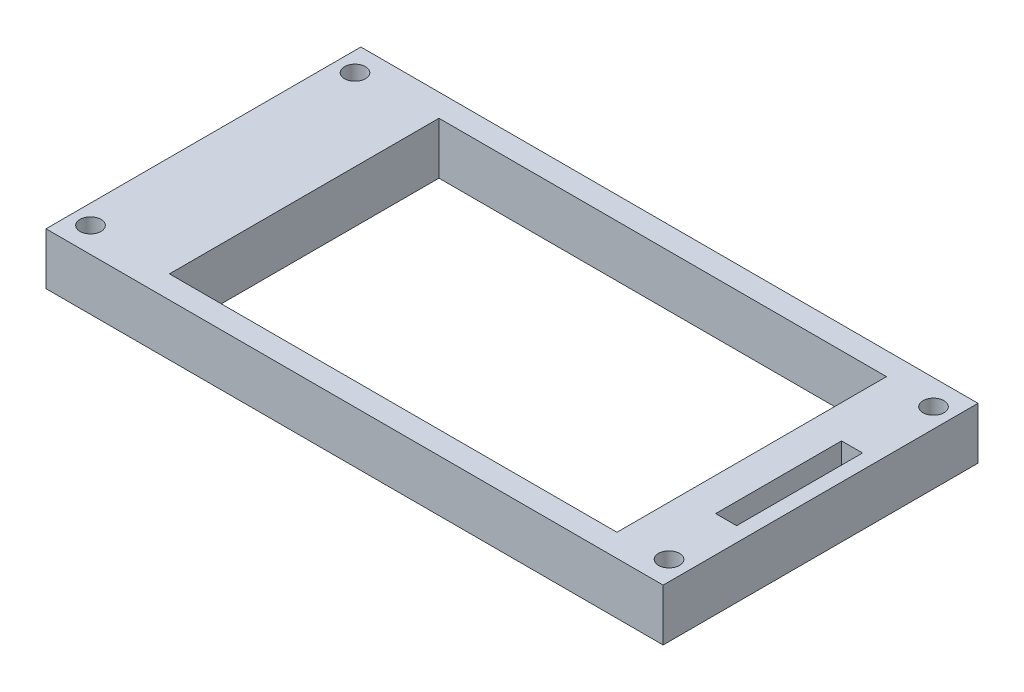
SolidWorks part; units mm, degrees
ref_plane "Front" through (0, 0, 0) normal (0, 0, 1) x (1, 0, 0)
ref_plane "Top" through (0, 0, 0) normal (0, 1, 0) x (1, 0, 0)
ref_plane "Right" through (0, 0, 0) normal (1, 0, 0) x (0, 0, -1)
sketch "Sketch1" plane through (0, 0, 0) normal (0, 1, 0) x (1, 0, 0)
  line L0 (12, -2.7) -> (65.3, -2.7)
  line L1 (0, 0) -> (73.5, 0)
  line L2 (0, 0) -> (0, -37.5)
  line L3 (0, -37.5) -> (73.5, -37.5)
  line L4 (73.5, 0) -> (73.5, -37.5)
  line L5 (69.25, -12) -> (71.75, -12)
  line L6 (69.25, -12) -> (69.25, -27)
  line L7 (69.25, -27) -> (71.75, -27)
  line L8 (71.75, -12) -> (71.75, -27)
  line L9 (4, 0) -> (68.1, 0)
  line L10 (4, 0) -> (4, -37.5)
  line L11 (4, -37.5) -> (68.1, -37.5)
  line L12 (68.1, 0) -> (68.1, -37.5)
  line L13 (12, -2.7) -> (12, -34.8)
  line L14 (12, -34.8) -> (65.3, -34.8)
  line L15 (65.3, -2.7) -> (65.3, -34.8)
  circle A0 centre (2.3, -3) radius 1.25
  circle A1 centre (71.2, -3) radius 1.25
  circle A2 centre (71.2, -34.5) radius 1.25
  circle A3 centre (2.3, -34.5) radius 1.25
  point P17 (70.5, -12)
  point P18 (70.5, -27)
  point P23 (68.1, -18.75)
  dimension "D3" = 2.5
  dimension "D4" = 3
  dimension "D5" = 2.3
  dimension "D6" = 2.5
  dimension "D7" = 3
  dimension "D8" = 2.3
  dimension "D9" = 2.5
  dimension "D10" = 3
  dimension "D11" = 2.3
  dimension "D12" = 2.5
  dimension "D13" = 3
  dimension "D14" = 2.3
  dimension "D1" = 37.5
  dimension "D2" = 73.5
  dimension "D15" = 2.5
  dimension "D16" = 15
  dimension "D17" = 12
  dimension "D18" = 3
  dimension "D19" = 37.5
  dimension "D20" = 64.1
  dimension "D21" = 5.4
  dimension "D22" = 53.3
  dimension "D23" = 2.7
  dimension "D24" = 2.7
  dimension "D25" = 8.2
extrude "Boss-Extrude1" add sketch "Sketch1" along normal blind 6.18 contours L10 L1 L2 L3 A3 A0 | L12 L1 L10 L3 | L1 L12 L3 L4 A2 A1 L5 L8 L7 L6
